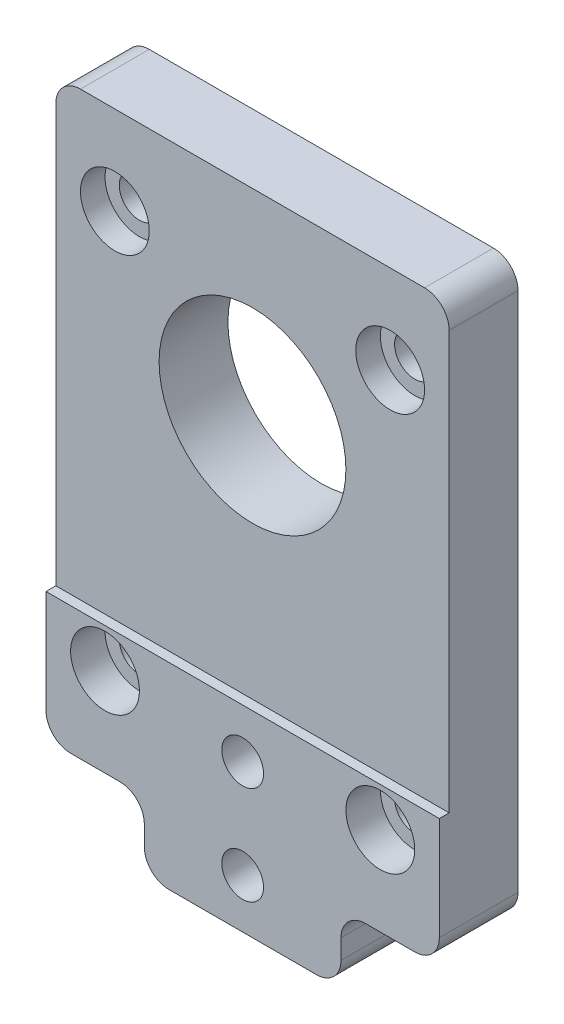
SolidWorks part; units mm, degrees
ref_plane "Front Plane" through (0, 0, 0) normal (0, 0, 1) x (1, 0, 0)
ref_plane "Top Plane" through (0, 0, 0) normal (0, 1, 0) x (1, 0, 0)
ref_plane "Right Plane" through (0, 0, 0) normal (1, 0, 0) x (0, 0, -1)
sketch "Sketch1" plane through (0, 0, 0) normal (0, 0, 1) x (1, 0, 0)
  line L0 (0, -353.8104) -> (0, 17336.7087) construction
  line L1 (-10, -15) -> (-10, 15)
  line L2 (-10, 15) -> (-15, 30)
  line L3 (10, -15) -> (-10, -15)
  line L4 (10, -15) -> (10, 15)
  line L5 (10, 15) -> (15, 30)
  arc A0 (15, 30) -> (-15, 30) centre (0, 30) ccw
  circle A1 centre (0, 0) radius 2.125
  circle A2 centre (0, -10) radius 2.125
  dimension "D1" = 4.25
  dimension "D2" = 4.25
  dimension "D3" = 10
  dimension "D4" = 30
  dimension "D5" = 30
  dimension "D7" = 30
  dimension "D6" = 5
  dimension "D8" = 20
  dimension "D9" = 10
  dimension "D10" = 30
extrude "Boss-Extrude2" add sketch "Sketch1" along normal blind 8
sketch "Sketch7" plane through (0, 0, 0) normal (0, 0, -1) x (-1, 0, 0)
  line L0 (0, -970) -> (0, 49030) construction
  line L1 (-20, 50) -> (20, 50)
  line L2 (-20, 50) -> (-20, -8)
  line L3 (-20, -8) -> (20, -8)
  line L4 (20, 50) -> (20, -8)
  arc A0 (15, 30) -> (-15, 30) centre (0, 30) ccw construction
  dimension "D1" = 40
  dimension "D2" = 58
  dimension "D3" = 20
  dimension "D4" = 20
extrude "Boss-Extrude3" add sketch "Sketch7" against normal up to surface (8 mm away) up to face at (2.125, 0, 8)
fillet "Fillet1" radius 2.5 8 edges at (10, -15, 4) (-10, -15, 4) (20, 50, 4) (10, -8, 4) (20, -8, 4) (-20, 50, 4) (-20, -8, 4) (-10, -8, 4)
sketch "Sketch3" plane through (0, 0, 8) normal (0, 0, 1) x (1, 0, 0)
  circle A0 centre (0, 30) radius 9.5
  dimension "D1" = 19
  dimension "D2" = 30
extrude "Cut-Extrude2" cut sketch "Sketch3" against normal through all
sketch "Sketch2" plane through (0, 0, 8) normal (0, 0, 1) x (1, 0, 0)
  line L0 (-1009.4328, 41) -> (48990.5672, 41) construction
  line L1 (-1007.6541, 1) -> (48992.3459, 1) construction
  line L2 (-14, -973.06) -> (-14, 49026.94) construction
  line L3 (14, -977.0128) -> (14, 49022.9872) construction
  line L4 (0, -970) -> (0, 49030) construction
  line L5 (-1000, 30) -> (49000, 30) construction
  line L6 (-17.5, 50) -> (17.5, 50) construction
  circle A0 centre (-14, 41) radius 2.05
  circle A1 centre (14, 41) radius 2.05
  circle A2 centre (14, 1) radius 2.05
  circle A3 centre (-14, 1) radius 2.05
  dimension "D3" = 9
  dimension "D4" = 40
  dimension "D5" = 4.1
  dimension "D6" = 4.1
  dimension "D7" = 4.1
  dimension "D8" = 4.1
  dimension "D1" = 14
  dimension "D2" = 14
extrude "Cut-Extrude1" cut sketch "Sketch2" against normal through all
sketch "Sketch6" plane through (0, 0, 8) normal (0, 0, 1) x (1, 0, 0)
  line L0 (-7.5, -15) -> (7.5, -15) construction
  line L1 (-30, 5) -> (30, 5)
  line L2 (-30, 5) -> (-30, 55)
  line L3 (-30, 55) -> (30, 55)
  line L4 (30, 5) -> (30, 55)
  line L5 (-30, 5) -> (30, 55) construction
  line L6 (-30, 55) -> (30, 5) construction
  point P0 (0, 30)
  dimension "D1" = 20
  dimension "D2" = 60
extrude "Cut-Extrude5" cut sketch "Sketch6" against normal blind 1
sketch "Sketch9" plane through (0, 0, 8) normal (0, 0, 1) x (1, 0, 0)
  circle A0 centre (0, -10) radius 2.125
  circle A1 centre (0, 0) radius 2.125
  dimension "D1" = 4.25
  dimension "D2" = 4.25
extrude "Cut-Extrude7" cut sketch "Sketch9" against normal through all
sketch "Sketch11" plane through (0, 0, 8) normal (0, 0, 1) x (1, 0, 0)
  circle A0 centre (-14, 1) radius 3.5
  circle A1 centre (14, 1) radius 3.5
  circle A2 centre (14, 41) radius 3.5
  circle A3 centre (-14, 41) radius 3.5
  dimension "D1" = 7
  dimension "D2" = 7
  dimension "D3" = 7
  dimension "D4" = 7
extrude "Cut-Extrude9" cut sketch "Sketch11" against normal blind 3.5
